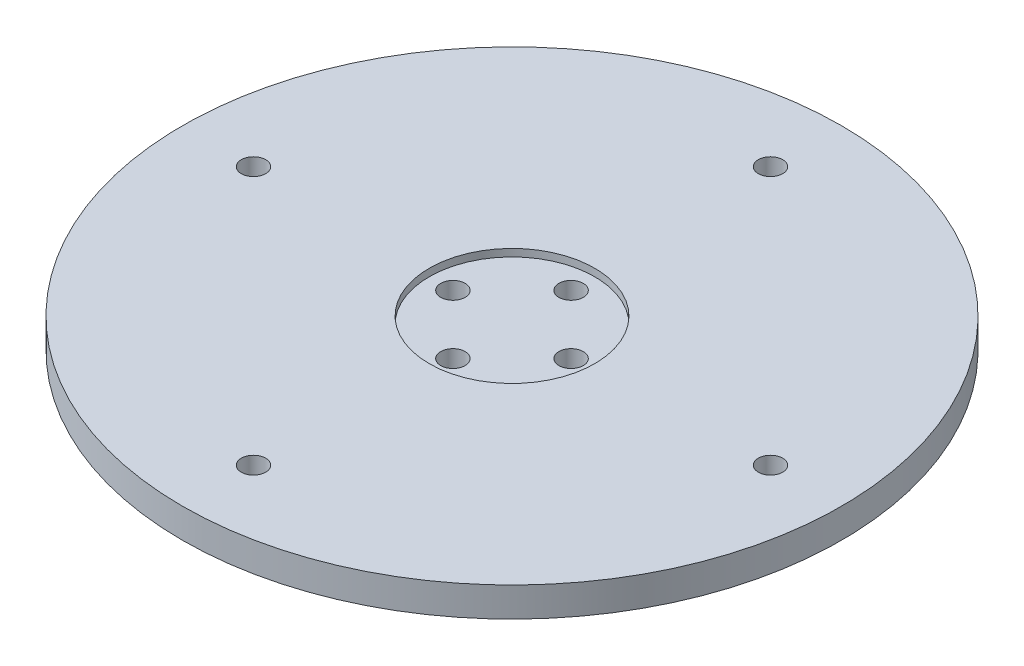
SolidWorks part; units mm, degrees
ref_plane "Front Plane" through (0, 0, 0) normal (0, 0, 1) x (1, 0, 0)
ref_plane "Top Plane" through (0, 0, 0) normal (0, 1, 0) x (1, 0, 0)
ref_plane "Right Plane" through (0, 0, 0) normal (1, 0, 0) x (0, 0, -1)
sketch "Sketch1" plane through (0, 0, 0) normal (0, 1, 0) x (1, 0, 0)
  circle A0 centre (0, 0) radius 44.6177
  circle A1 centre (0, 8) radius 1.65
  circle A2 centre (8, 0) radius 1.65
  circle A3 centre (0, -8) radius 1.65
  circle A4 centre (-8, 0) radius 1.65
  circle A5 centre (0, 35) radius 1.65
  circle A6 centre (35, 0) radius 1.65
  circle A7 centre (0, -35) radius 1.65
  circle A8 centre (-35, 0) radius 1.65
  point P14 (0, 0)
  point P23 (0, 0)
  dimension "D1" = 8
  dimension "D3" = 35
  dimension "D2" = 4
  dimension "D4" = 4
extrude "Boss-Extrude1" add sketch "Sketch1" along normal blind 4
sketch "Sketch2" plane through (0, 4, 0) normal (0, 1, 0) x (1, 0, 0)
  circle A0 centre (0, 0) radius 11.2
extrude "Cut-Extrude1" cut sketch "Sketch2" against normal blind 1
